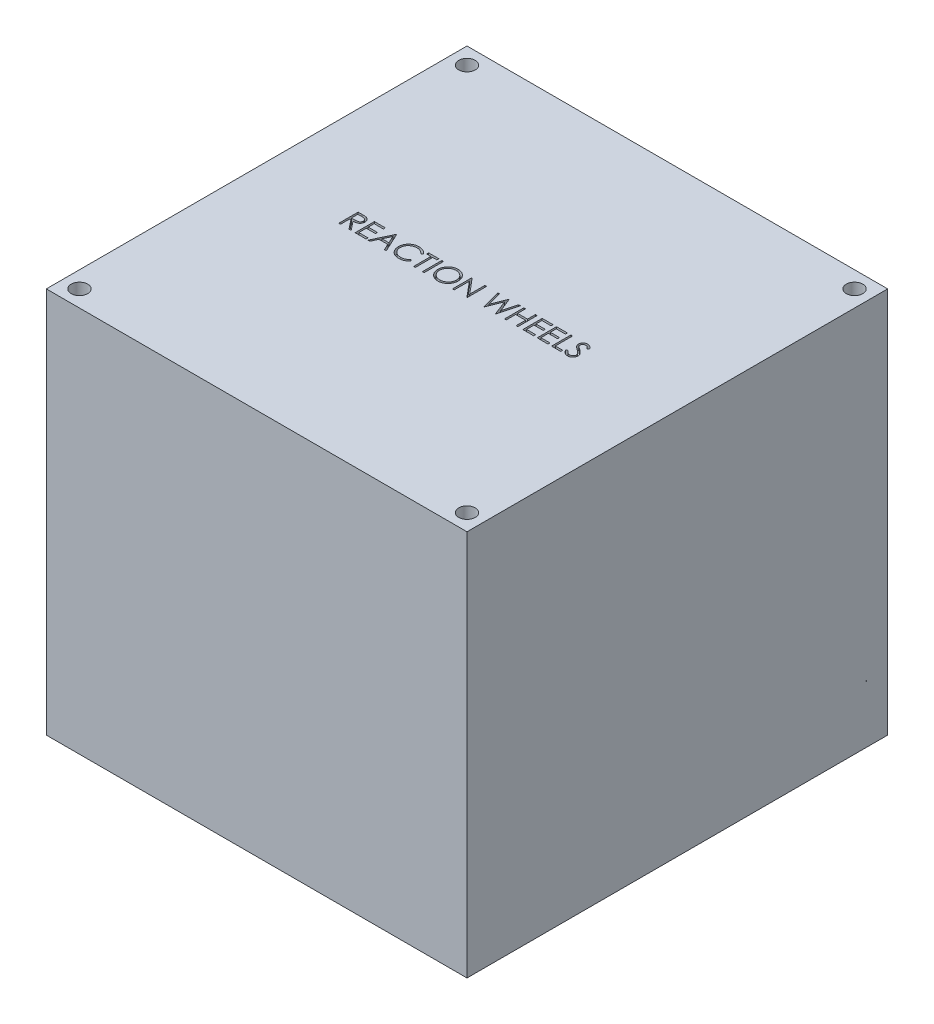
SolidWorks part; units mm, degrees
material "1060 Alloy"
ref_plane "Front Plane" through (0, 0, 0) normal (0, 0, 1) x (1, 0, 0)
ref_plane "Top Plane" through (0, 0, 0) normal (0, 1, 0) x (1, 0, 0)
ref_plane "Right Plane" through (0, 0, 0) normal (1, 0, 0) x (0, 0, -1)
sketch "Sketch1" plane through (0, 0, 0) normal (0, 1, 0) x (1, 0, 0)
  line L1 (-38.1, -38.1) -> (38.1, -38.1)
  line L2 (-38.1, -38.1) -> (-38.1, 38.1)
  line L3 (-38.1, 38.1) -> (38.1, 38.1)
  line L4 (38.1, -38.1) -> (38.1, 38.1)
  line L5 (-38.1, -38.1) -> (38.1, 38.1) construction
  line L6 (-38.1, 38.1) -> (38.1, -38.1) construction
  point P0 (0, 0)
  dimension "D1" = 76.2
  dimension "D2" = 76.2
extrude "Bulk" add sketch "Sketch1" along normal blind 70
sketch "Sketch2" plane through (0, 70, 0) normal (0, 1, 0) x (1, 0, 0)
  line L0 (-38.1, 38.1) -> (38.1, -38.1) construction
  line L1 (38.1, -38.1) -> (38.1, 38.1) construction
  line L2 (38.1, 38.1) -> (-38.1, -38.1) construction
  line L5 (-38.1, 38.1) -> (-38.1, -38.1) construction
  line L6 (38.1, 38.1) -> (-38.1, 38.1) construction
  line L7 (-38.1, -38.1) -> (38.1, -38.1) construction
  circle A0 centre (-35.1, 35.1) radius 1.5
  circle A1 centre (35.1, 35.1) radius 1.5
  circle A2 centre (35.1, -35.1) radius 1.5
  circle A3 centre (-35.1, -35.1) radius 1.5
  dimension "D1" = 3
  dimension "D2" = 3
  dimension "D3" = 3
  dimension "D4" = 3
  dimension "D7" = 3
  dimension "D5" = 3
  dimension "D6" = 3
  dimension "D8" = 3
extrude "Mounting Holes" cut sketch "Sketch2" against normal blind 78.75
sketch "Sketch3" plane through (0, 70, 0) normal (0, 1, 0) x (1, 0, 0)
  text T0 "REACTION WHEELS"
extrude "Label" cut sketch "Sketch3" against normal blind 1
sketch "Sketch4" plane through (0, 0, 0) normal (0, -1, 0) x (1, 0, 0)
  line L0 (-38.1, 38.1) -> (38.1, -38.1) construction
  line L1 (38.1, -38.1) -> (38.1, 38.1) construction
  line L2 (38.1, 38.1) -> (-38.1, -38.1) construction
  line L4 (-0.5, -0.5) -> (0.5, -0.5)
  line L5 (-0.5, -0.5) -> (-0.5, 0.5)
  line L6 (-0.5, 0.5) -> (0.5, 0.5)
  line L7 (0.5, -0.5) -> (0.5, 0.5)
  line L8 (-0.5, -0.5) -> (0.5, 0.5) construction
  line L9 (-0.5, 0.5) -> (0.5, -0.5) construction
  line L10 (-0.6, -0.6) -> (0.6, -0.6)
  line L11 (-0.6, -0.6) -> (-0.6, 0.6)
  line L12 (-0.6, 0.6) -> (0.6, 0.6)
  line L13 (0.6, -0.6) -> (0.6, 0.6)
  line L14 (-0.6, -0.6) -> (0.6, 0.6) construction
  line L15 (-0.6, 0.6) -> (0.6, -0.6) construction
  point P4 (0, 0)
  point P15 (0, 0)
  dimension "D1" = 1
  dimension "D2" = 0.1
extrude "Alignmnet fixing" cut sketch "Sketch4" against normal blind 10
